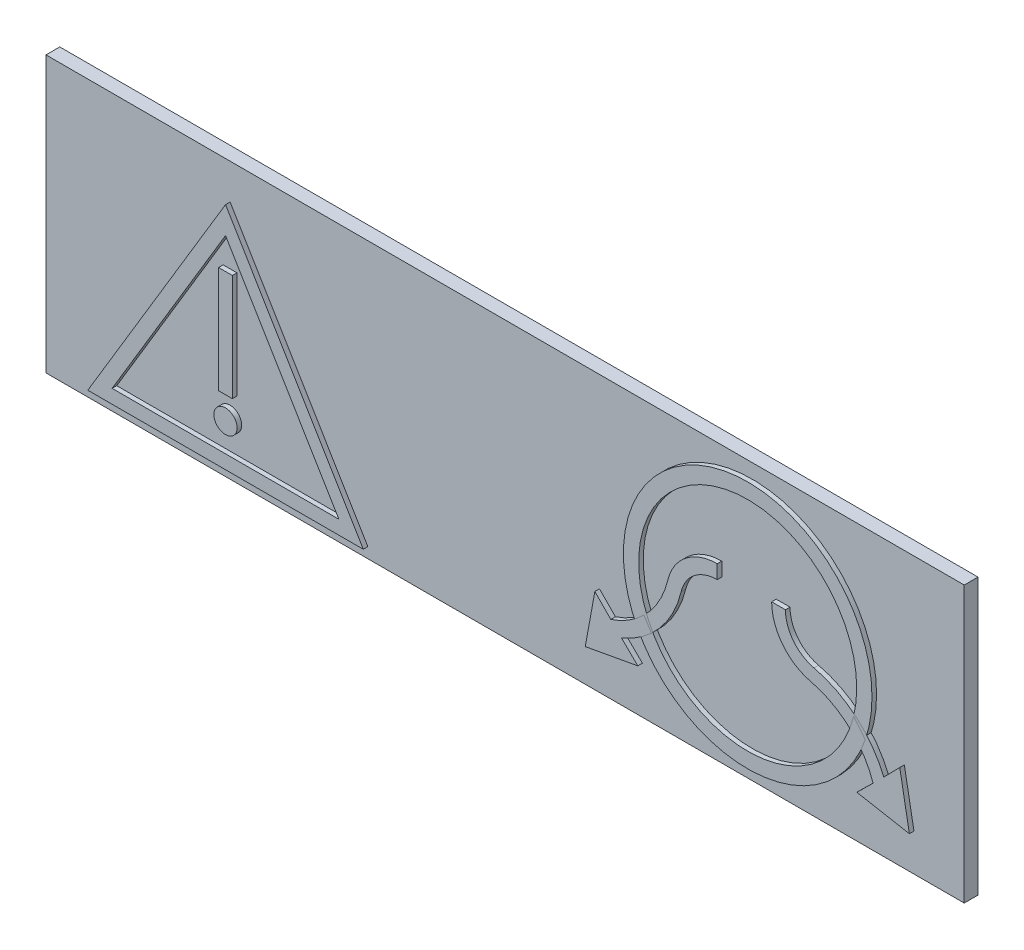
SolidWorks part; units mm, degrees
ref_plane "Face" through (0, 0, 0) normal (0, 0, 1) x (1, 0, 0)
ref_plane "Dessus" through (0, 0, 0) normal (0, 1, 0) x (1, 0, 0)
ref_plane "Droite" through (0, 0, 0) normal (1, 0, 0) x (0, 0, -1)
sketch "Esquisse1" plane through (0, 0, 0) normal (0, 0, 1) x (1, 0, 0)
  line L1 (-18.4597, -45.2714) -> (-18.4597, -26.5274) construction
  line L2 (-28.4597, -36.4119) -> (-8.4597, -36.4119)
  line L3 (-28.4597, -36.4119) -> (-28.4597, -42.4119)
  line L4 (-8.4597, -36.4119) -> (-8.4597, -42.4119)
  line L10 (-28.4597, -42.4119) -> (-8.4597, -42.4119)
  dimension "D3" = 10
  dimension "D1" = 6
  dimension "D2" = 10
extrude "Extrusion1" add sketch "Esquisse1" against normal blind 0.3
ref_plane "Plan1" through (0, 0, 0.1) normal (0, 0, 1) x (1, 0, 0)
sketch "Esquisse2" plane through (0, 0, 0.1) normal (0, 0, 1) x (1, 0, 0)
  line L0 (-26.8193, -41.7823) -> (-24.3492, -37.6654)
  line L1 (-24.3492, -37.6654) -> (-21.8791, -41.7823)
  line L2 (-26.8193, -41.7823) -> (-21.8791, -41.7823)
  line L3 (-27.3492, -42.0823) -> (-21.3492, -42.0823)
  line L4 (-27.3492, -42.0823) -> (-24.3492, -37.0823)
  line L5 (-24.3492, -37.0823) -> (-21.3492, -42.0823)
extrude "Extrusion2" add sketch "Esquisse2" along normal blind 0.1
sketch "Esquisse4" plane through (-58.0975, -20.934, 0.1) normal (0, 0, 1) x (1, 0, 0)
  line L2 (33.747, -16.7185) -> (33.747, -20.8354) construction
  line L4 (33.597, -17.4094) -> (33.897, -17.4094)
  line L5 (33.597, -17.4094) -> (33.597, -19.734)
  line L8 (33.597, -19.734) -> (33.897, -19.734)
  line L9 (33.897, -17.4094) -> (33.897, -19.734)
  circle A0 centre (33.747, -20.2333) radius 0.2524
  dimension "D1" = 0.3
  dimension "D2" = 0.15
sketch "Esquisse5" plane through (0, 0, 0.1) normal (0, 0, 1) x (1, 0, 0)
  line L0 (-15.9299, -39.331) -> (-9.4928, -39.331) construction
  line L4 (-12.9762, -37.9711) -> (-12.9762, -40.8213) construction
  circle A0 centre (-12.9762, -39.331) radius 2.7075
  circle A1 centre (-12.9762, -39.331) radius 2.375
  point P9 (-15.1453, -39.331)
sketch "Esquisse6" plane through (0, 0, 0.1) normal (0, 0, 1) x (1, 0, 0)
  line L0 (-16.5143, -41.5008) -> (-12.989, -37.9756) construction
  line L1 (-10.2449, -40.9434) -> (-10.5991, -41.2915)
  line L2 (-15.9568, -40.7104) -> (-16.305, -40.3562)
  line L3 (-16.305, -40.3562) -> (-16.5143, -41.5008)
  line L4 (-13.6399, -38.5009) -> (-13.6399, -38.8009)
  line L5 (-15.3696, -41.2915) -> (-16.5143, -41.5008)
  line L6 (-15.7239, -40.9434) -> (-15.3696, -41.2915)
  line L7 (-10.0119, -40.7104) -> (-9.6638, -40.3562)
  line L8 (-12.989, -37.1279) -> (-12.989, -42.4337) construction
  line L9 (-9.6638, -40.3562) -> (-9.4545, -41.5008)
  line L10 (-10.5991, -41.2915) -> (-9.4545, -41.5008)
  line L11 (-12.4544, -38.6264) -> (-12.1544, -38.6264)
  line L12 (-13.8274, -37.9756) -> (-8.5216, -37.9756) construction
  arc A0 (-15.7239, -40.9434) -> (-14.4258, -39.4219) centre (-16.5614, -38.9143) ccw
  arc A1 (-14.4258, -39.4219) -> (-13.6399, -38.8009) centre (-13.6399, -39.6087) cw
  arc A2 (-15.9568, -40.7104) -> (-14.7177, -39.3525) centre (-16.5614, -38.9143) ccw
  arc A3 (-14.7177, -39.3525) -> (-13.6399, -38.5009) centre (-13.6399, -39.6087) cw
  arc A4 (-10.0119, -40.7104) -> (-11.5334, -39.4123) centre (-12.041, -41.5479) ccw
  arc A5 (-10.2449, -40.9434) -> (-11.6028, -39.7042) centre (-12.041, -41.5479) ccw
  arc A6 (-11.6028, -39.7042) -> (-12.4544, -38.6264) centre (-11.3466, -38.6264) cw
  arc A7 (-11.5334, -39.4123) -> (-12.1544, -38.6264) centre (-11.3466, -38.6264) cw
  point P9 (-14.3241, -38.9302)
  point P17 (-12.989, -39.9727)
  dimension "D1" = 1.8623
extrude "Extrusion3" add sketch "Esquisse4" along normal blind 0.1
extrude "Extrusion4" add sketch "Esquisse5" along normal blind 0.1
extrude "Extrusion5" add sketch "Esquisse6" along normal blind 0.1
